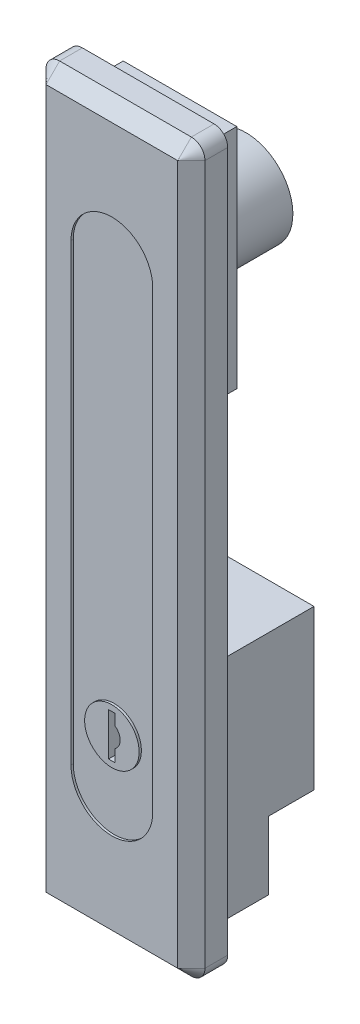
SolidWorks part; units mm, degrees
ref_plane "Спереди" through (0, 0, 0) normal (0, 0, 1) x (1, 0, 0)
ref_plane "Сверху" through (0, 0, 0) normal (0, 1, 0) x (1, 0, 0)
ref_plane "Справа" through (0, 0, 0) normal (1, 0, 0) x (0, 0, -1)
sketch "Эскиз1" plane through (0, 0, 0) normal (0, 0, 1) x (1, 0, 0)
  line L0 (0, 0) -> (0, 14.4724) construction
  line L1 (-17.5, 80) -> (17.5, 80)
  line L2 (-17.5, 80) -> (-17.5, -80)
  line L3 (-17.5, -80) -> (17.5, -80)
  line L4 (17.5, 80) -> (17.5, -80)
  line L5 (0, 0) -> (10.2218, 0) construction
  dimension "D1" = 35
  dimension "D2" = 160
extrude "Вытянуть1" add sketch "Эскиз1" along normal blind 8
fillet "Скругление1" radius 3 4 edges at (-17.5, -80, 4) (17.5, -80, 4) (-17.5, 80, 4) (17.5, 80, 4)
chamfer "Фаска1" distance 3 angle 45 8 edges at (-17.5, 0, 8) (-16.6213, -79.1213, 8) (-16.6213, 79.1213, 8) (0, -80, 8) (0, 80, 8) (16.6213, -79.1213, 8) (16.6213, 79.1213, 8) (17.5, 0, 8)
sketch "Эскиз2" plane through (0, 0, 8) normal (0, 0, 1) x (1, 0, 0)
  line L0 (0, 0) -> (0, 18.7208) construction
  line L2 (-9, 50) -> (-9, -50)
  line L4 (9, 50) -> (9, -50)
  line L5 (0, 0) -> (25.3143, 0) construction
  arc A0 (9, 50) -> (-9, 50) centre (0, 50) ccw
  arc A1 (-9, -50) -> (9, -50) centre (0, -50) ccw
  dimension "D1" = 100
  dimension "D2" = 18
extrude "Вырез-Вытянуть1" cut sketch "Эскиз2" against normal blind 0.5
sketch "Эскиз3" plane through (0, 0, 7.5) normal (0, 0, 1) x (1, 0, 0)
  circle A0 centre (0, -40) radius 6
  dimension "D1" = 12
  dimension "D2" = 40
extrude "Вытянуть2" add sketch "Эскиз3" along normal blind 0.5
sketch "Эскиз4" plane through (0, 0, 0) normal (0, 0, -1) x (-1, 0, 0)
  line L0 (0, 0) -> (0, 17.3079) construction
  line L1 (-12.5, 75) -> (12.5, 75)
  line L2 (-12.5, 75) -> (-12.5, -75)
  line L3 (-12.5, -75) -> (12.5, -75)
  line L4 (12.5, 75) -> (12.5, -75)
  line L5 (0, 0) -> (24.3723, 0) construction
  dimension "D1" = 25
  dimension "D2" = 150
extrude "Вытянуть3" add sketch "Эскиз4" along normal blind 24
sketch "Эскиз6" plane through (0, 0, -24) normal (0, 0, -1) x (-1, 0, 0)
  line L0 (-12.5, 75) -> (-12.5, -75) construction
  line L1 (-12.5, 25) -> (12.5, 25)
  line L2 (-12.5, 25) -> (-12.5, -25)
  line L3 (-12.5, -25) -> (12.5, -25)
  line L4 (12.5, 25) -> (12.5, -25)
  line L5 (12.5, -75) -> (12.5, 75) construction
  line L6 (12.5, 75) -> (-12.5, 75) construction
  line L7 (-12.5, -75) -> (12.5, -75) construction
  dimension "D1" = 50
  dimension "D2" = 50
extrude "Вырез-Вытянуть3" cut sketch "Эскиз6" against normal blind 24
sketch "Эскиз8" plane through (12.5, 0, 0) normal (1, 0, 0) x (0, 0, -1)
  line L1 (24, -75) -> (14, -75)
  line L2 (24, -75) -> (24, -60)
  line L3 (24, -60) -> (14, -60)
  line L4 (14, -75) -> (14, -60)
  dimension "D1" = 10
  dimension "D2" = 15
extrude "Вырез-Вытянуть4" cut sketch "Эскиз8" against normal through all
sketch "Эскиз9" plane through (0, 0, -24) normal (0, 0, -1) x (-1, 0, 0)
  line L1 (17.5, 77) -> (17.5, -77) construction
  line L2 (12.5, 50) -> (0, 50) construction
  line L3 (-12.5, 75) -> (12.5, 75)
  line L4 (-12.5, 75) -> (-12.5, 25)
  line L5 (-12.5, 25) -> (12.5, 25)
  line L6 (12.5, 75) -> (12.5, 25)
  line L7 (12.5, 25) -> (12.5, 75) construction
  line L8 (12.5, 25) -> (12.5, 75) construction
  line L9 (12.5, 75) -> (-12.5, 75) construction
  line L10 (12.5, 75) -> (-12.5, 75) construction
  circle A0 centre (0, 50) radius 10.35
  dimension "D2" = 17.5
  dimension "D3" = 20.7
extrude "Вырез-Вытянуть5" cut sketch "Эскиз9" against normal up to surface (24 mm away) up to face at (0, -50, 0)
sketch "Эскиз10" plane through (0, 0, -14) normal (0, 0, -1) x (-1, 0, 0)
  line L0 (0, -75) -> (0, -60) construction
  line L1 (12.5, -75) -> (-12.5, -75) construction
  line L2 (12.5, -60) -> (-12.5, -60) construction
  circle A0 centre (0, -69) radius 2
  dimension "D1" = 6
  dimension "D2" = 4
extrude "Вырез-Вытянуть6" cut sketch "Эскиз10" against normal blind 4
sketch "Эскиз11" plane through (0, 0, 0) normal (0, 0, -1) x (-1, 0, 0)
  line L0 (0, 50) -> (0, 0) construction
  line L1 (-12.5, 75) -> (12.5, 75)
  line L2 (-12.5, 75) -> (-12.5, 25)
  line L3 (-12.5, 25) -> (12.5, 25)
  line L4 (12.5, 75) -> (12.5, 25)
  line L5 (-12.5, 75) -> (12.5, 25) construction
  line L6 (-12.5, 25) -> (12.5, 75) construction
  line L7 (-12.5, -25) -> (12.5, -25) construction
  point P0 (0, 50)
  dimension "D1" = 25
  dimension "D2" = 50
  dimension "D3" = 50
extrude "Бобышка-Вытянуть2" add sketch "Эскиз11" along normal blind 7
sketch "Эскиз12" plane through (0, 0, 8) normal (0, 0, 1) x (1, 0, 0)
  line L1 (-0.7385, -35.2865) -> (0.7385, -35.2865)
  line L2 (-0.7385, -35.2865) -> (-0.7385, -44.7135)
  line L3 (-0.7385, -44.7135) -> (0.7385, -44.7135)
  line L4 (0.7385, -35.2865) -> (0.7385, -44.7135)
  line L5 (-0.7385, -35.2865) -> (0.7385, -44.7135) construction
  line L6 (-0.7385, -44.7135) -> (0.7385, -35.2865) construction
  arc A0 (0.7385, -37.7352) -> (0.7385, -42.0019) centre (-0.8321, -39.8685) cw
  point P0 (0, -40)
extrude "Вырез-Вытянуть7" cut sketch "Эскиз12" against normal blind 5 contours L4 L1 L2 L3 | A0 L4
hole_wizard "Отверстие обработанное метчиком M61" positions "Эскиз15" profile "Эскиз14" tap size "M6" standard "DIN"
sketch "Эскиз15" plane through (0, 0, -24) normal (0, 0, -1) x (-1, 0, 0)
  point P0 (0, 50)
sketch "Эскиз14" plane through (0, 50, -24) normal (1, 0, 0) x (0, 1, 0)
  line L0 (0, 0) -> (0, 18.5022)
  line L1 (0, 18.5022) -> (2.5, 17)
  line L2 (2.5, 17) -> (2.5, 0)
  line L5 (2.5, 0) -> (0, 0)
  line L10 (0, 18.5022) -> (-2.5, 17) construction
  line L11 (0, -6.35) -> (0, 107.95) construction
  dimension "Диаметр сверла" = 5
  dimension "Глубина сверла" = 17
  dimension "Угол заточки сверла" = 118
cosmetic thread "Отверстие резьбы1" parameters "D1"=12, "D2"=6
sketch "Эскиз16" plane through (0, 0, -7) normal (0, 0, -1) x (-1, 0, 0)
  line L0 (0, 25) -> (0, 31) construction
  line L1 (-12.5, 25) -> (12.5, 25) construction
  line L2 (0, 50) -> (12.5, 50) construction
  line L3 (12.5, 25) -> (12.5, 75) construction
  circle A0 centre (0, 31) radius 2
  circle A2 centre (0, 69) radius 2
  dimension "D1" = 4
  dimension "D2" = 38
extrude "Вырез-Вытянуть8" cut sketch "Эскиз16" against normal blind 7.5
sketch "Эскиз17" plane through (0, 0, -24) normal (0, 0, -1) x (-1, 0, 0)
  line L1 (4, 46) -> (-4, 46)
  line L2 (4, 46) -> (4, 54)
  line L3 (4, 54) -> (-4, 54)
  line L4 (-4, 46) -> (-4, 54)
  line L5 (4, 46) -> (-4, 54) construction
  line L6 (4, 54) -> (-4, 46) construction
  circle A0 centre (0, 50) radius 10.35
  circle A1 centre (0, 50) radius 10.35 construction
  point P0 (0, 50)
  dimension "D1" = 8
extrude "Вырез-Вытянуть9" cut sketch "Эскиз17" against normal blind 2.5
sketch "Эскиз18" plane through (0, 0, -21.5) normal (0, 0, -1) x (-1, 0, 0)
  line L0 (0, 44.3431) -> (0, 39.65)
  line L1 (5.6569, 50) -> (10.35, 50)
  arc A0 (0, 39.65) -> (10.35, 50) centre (0, 50) ccw
  circle A1 centre (0, 50) radius 10.35 construction
  arc A2 (0, 44.3431) -> (5.6569, 50) centre (0, 50) ccw
extrude "Вырез-Вытянуть10" cut sketch "Эскиз18" against normal blind 3.5
